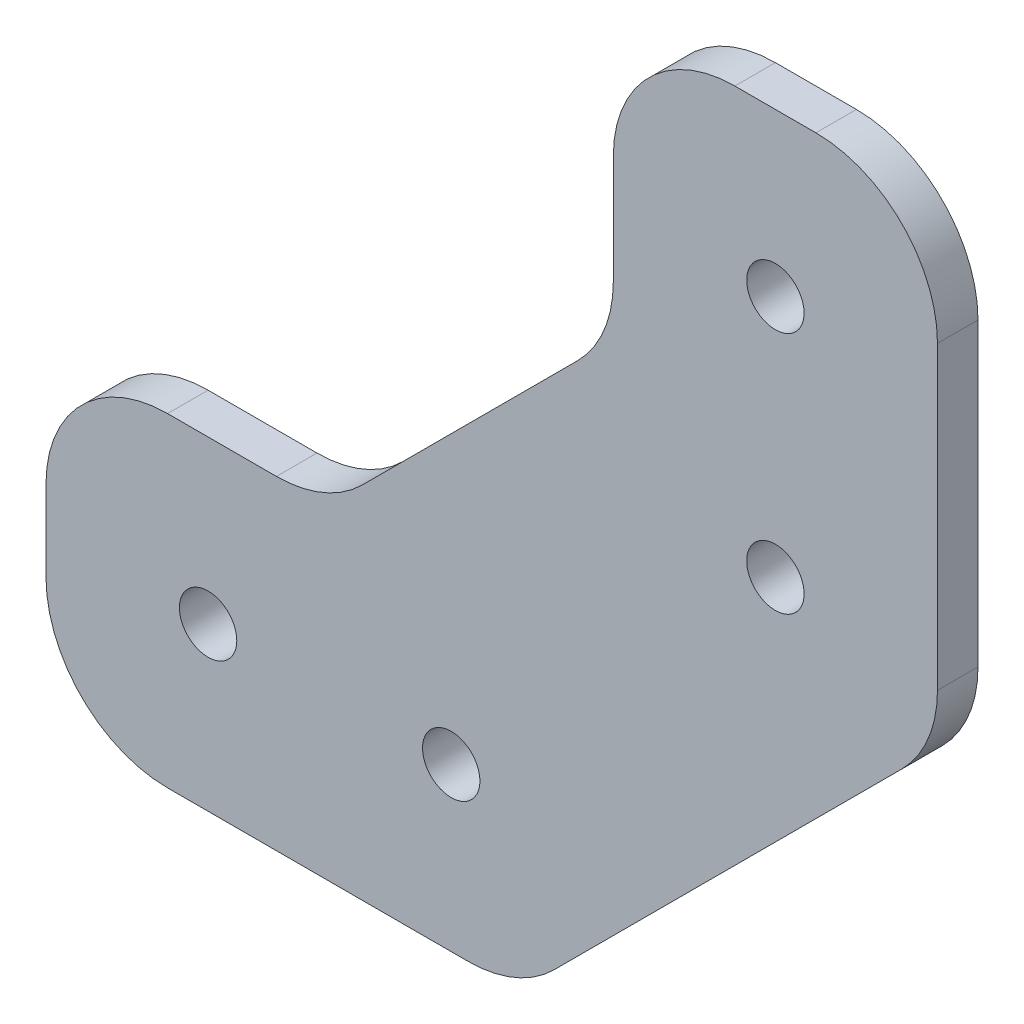
SolidWorks part; units mm, degrees
ref_plane "Front Plane" through (0, 0, 0) normal (0, 0, 1) x (1, 0, 0)
ref_plane "Top Plane" through (0, 0, 0) normal (0, 1, 0) x (1, 0, 0)
ref_plane "Right Plane" through (0, 0, 0) normal (1, 0, 0) x (0, 0, -1)
sketch "Sketch2" plane through (0, 0, 0) normal (0, 0, 1) x (1, 0, 0)
  line L0 (37.0105, 0) -> (69.85, 32.8395)
  line L1 (69.85, 32.8395) -> (69.85, 69.85)
  line L2 (69.85, 69.85) -> (44.45, 69.85)
  line L3 (44.45, 69.85) -> (44.45, 47.8506)
  line L4 (44.45, 47.8506) -> (21.9994, 25.4)
  line L5 (21.9994, 25.4) -> (0, 25.4)
  line L6 (0, 25.4) -> (0, 0)
  line L7 (0, 0) -> (37.0105, 0)
  line L9 (0, 12.7) -> (-50000, 12.7) construction
  line L10 (57.15, 68.6866) -> (57.15, 50068.6866) construction
  line L11 (31.6316, 38.2184) -> (-35323.7074, 35393.5574) construction
  line L12 (57.15, 38.1) -> (57.15, 57.15) construction
  line L13 (31.75, 12.7) -> (12.7, 12.7) construction
  point P10 (31.75, 12.7)
  point P13 (57.15, 38.1)
  point P19 (57.15, 69.85)
  point P20 (57.15, 12.7)
  point P23 (33.2247, 36.6253)
  dimension "D1" = 45
  dimension "D2" = 25.4
  dimension "D3" = 25.4
  dimension "D4" = 19.05
  dimension "D5" = 12.7
  dimension "D6" = 12.7
  dimension "D7" = 31.75
extrude "Boss-Extrude1" add sketch "Sketch2" along normal mid plane 3.175
fillet "Fillet1" radius 9.525 8 edges at (69.85, 32.8395, 0) (37.0105, 0, 0) (0, 0, 0) (69.85, 69.85, 0) (44.45, 69.85, 0) (44.45, 47.8506, 0) (21.9994, 25.4, 0) (0, 25.4, 0)
hole_wizard "#8 Clearance Hole1" positions "Sketch4" profile "Sketch5" hole size "#8" standard "ANSI Inch" end condition through all
sketch "Sketch4" plane through (0, 0, 1.5875) normal (0, 0, 1) x (1, 0, 0)
  point P0 (12.7, 12.7)
  point P2 (31.75, 12.7)
  point P4 (57.15, 38.1)
  point P6 (57.15, 57.15)
sketch "Sketch5" plane through (12.7, 12.7, 1.5875) normal (1, 0, 0) x (0, -1, 0)
  line L0 (0, 0) -> (0, 3.175)
  line L1 (0, 3.175) -> (2.2479, 3.175)
  line L2 (2.2479, 3.175) -> (2.2479, 0)
  line L5 (2.2479, 0) -> (0, 0)
  line L11 (0, -6.35) -> (0, 107.95) construction
  dimension "Thru Hole Dia." = 4.4958
  dimension "Thru Hole Depth" = 3.175
